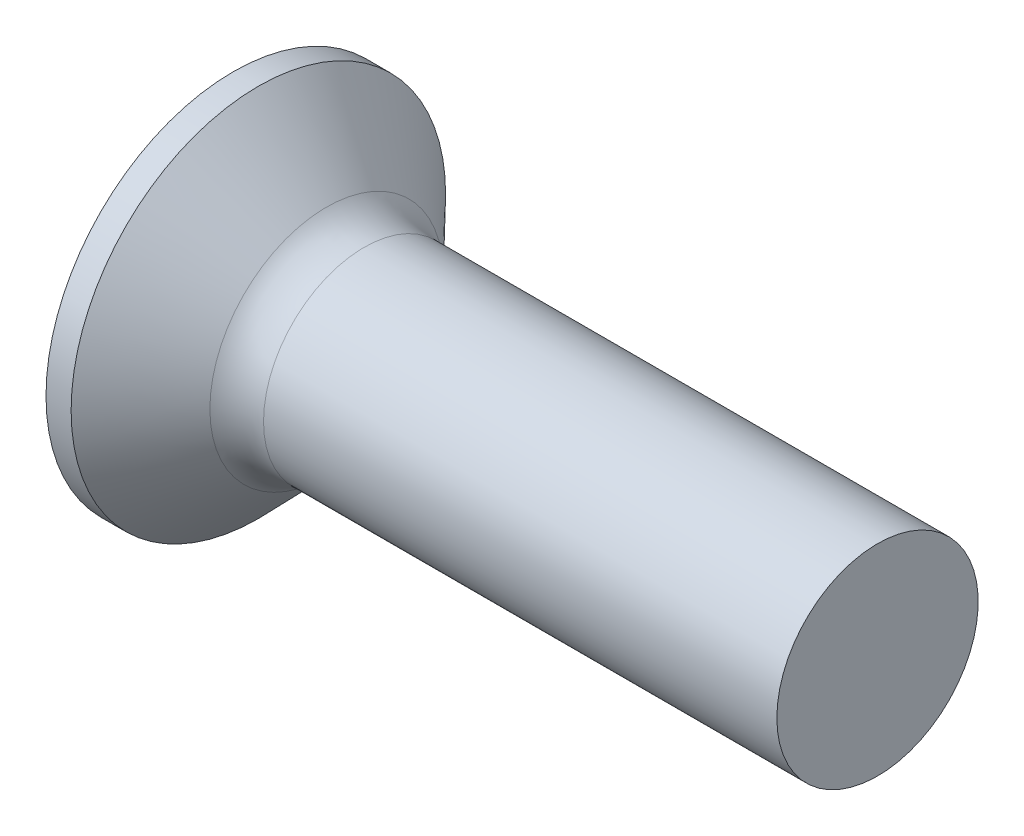
SolidWorks part; units mm, degrees
ref_plane "Plane1" through (0, 0, 0) normal (0, 0, 1) x (1, 0, 0)
ref_plane "Plane2" through (0, 0, 0) normal (0, 1, 0) x (1, 0, 0)
ref_plane "Plane3" through (0, 0, 0) normal (1, 0, 0) x (0, 0, -1)
sketch "BodySke" plane through (0, 0, 0) normal (0, 0, 1) x (1, 0, 0)
  line L0 (0, 0) -> (0, 4.65)
  line L1 (0, 4.65) -> (0.6238, 4.65)
  line L2 (2.7, 2.5) -> (16, 2.5)
  line L3 (16, 2.5) -> (16, 0)
  line L4 (16, 0) -> (0, 0)
  line L5 (-6.35, 0) -> (82.55, 0) construction
  line L6 (2.7, -2.5) -> (16, -2.5) construction
  line L7 (0.6238, -4.65) -> (2.7, -2.5) construction
  line L8 (0.6238, 4.65) -> (2.7, 2.5)
  line L9 (0, -4.65) -> (0.6238, -4.65) construction
  line L10 (3.5, 4.0875) -> (3.5, -5.4375) construction
  line L11 (0, 6.35) -> (0, -3.175) construction
  dimension "Diameter" = 5
  dimension "Length" = 16
  dimension "Head_ht" = 2.7
  dimension "Head_dia" = 9.3
  dimension "Head_ang" = 92
  dimension "D6" = 0.6238
  dimension "Advance" = 0.8
  dimension "Thread_nom" = 16
revolve "Base-Revolve" add sketch "BodySke" angle 360 about L5
cosmetic thread "ThreadCosmetic" [suppressed] parameters "Thread_length"=12.5, "Thread_minor"=4.11
fillet "Fillet1" radius 1.3
sketch "Sketch3" plane through (0, 0, 0) normal (-1, 0, 0) x (0, 0, 1)
  line L0 (-0.515, 2.45) -> (0.515, 2.45)
  line L1 (0.515, 2.45) -> (0.515, -2.45)
  line L2 (0.515, -2.45) -> (-0.515, -2.45)
  line L3 (-0.515, -2.45) -> (-0.515, 2.45)
  dimension "D1" = 2.45
  dimension "Cross_dia" = 4.9
  dimension "D2" = 0.515
  dimension "Cross_width" = 1.03
ref_plane "Plane4" through (3.05, 0, 0) normal (-1, 0, 0) x (0, 0, 1)
sketch "Sketch4" plane through (3.05, 0, 0) normal (-1, 0, 0) x (0, 0, 1)
  line L0 (-0.515, 0.9293) -> (0.515, 0.9293)
  line L3 (0.515, 0.9293) -> (0.515, -0.9293)
  line L4 (0.515, -0.9293) -> (-0.515, -0.9293)
  line L5 (-0.515, -0.9293) -> (-0.515, 0.9293)
  dimension "D1" = 1.03
  dimension "D2" = 1.8587
  dimension "D3" = 0.515
  dimension "D4" = 0.9293
loft "Recess" cut profiles "Sketch3", "Sketch4"
pattern_circular "RecPat" count 2 every 90 about axis through (-6.35, 0, 0) along (1, 0, 0)
sketch "RecCorSke" plane through (0, 0, 0) normal (0, 0, 1) x (1, 0, 0)
  line L0 (-3.175, 0) -> (15.875, 0) construction
  line L2 (0, 0) -> (0, 1.0643)
  line L3 (0, 1.0643) -> (3.05, 0.851)
  line L4 (3.05, 0.851) -> (3.3265, 0)
  line L5 (3.3265, 0) -> (0, 0)
  dimension "Diameter" = 1.702
  dimension "Depth" = 3.05
  dimension "Draft_angle" = 4
  dimension "Bottom_angle" = 18
revolve "RecessCore" cut sketch "RecCorSke" angle 360 about L0
sketch "ThdSchSke" plane through (0, 0, 0) normal (0, 0, 1) x (1, 0, 0)
  line L0 (3.5, -2.055) -> (3.1884, -2.5)
  line L1 (3.5, -2.055) -> (3.8116, -2.5)
  line L2 (3.8116, -2.5) -> (3.8116, -3.125)
  line L3 (-3.175, 0) -> (5.1513, 0) construction
  line L5 (3.8116, -3.125) -> (3.1884, -3.125)
  line L6 (3.1884, -3.125) -> (3.1884, -2.5)
  line L7 (0, 4.65) -> (0, -4.65) construction
  dimension "Thread_minor" = 4.11
  dimension "Diameter" = 5
  dimension "Start" = 3.5
  dimension "SideAngle" = 55
  dimension "VeeAngle" = 70
  dimension "Overcut" = 6.25
revolve "ThreadSchematic" [suppressed] cut sketch "ThdSchSke" angle 360 about L3
pattern_linear "ThdSchPat" [suppressed]
equation "\"D1@Sketch3\" = \"Cross_dia@Sketch3\" / 2"
equation "\"D2@Sketch3\" = \"Cross_width@Sketch3\" / 2"
equation "\"Depth@RecCorSke\" = \"Cross_depth@Plane4\""
equation "\"D1@Sketch4\" = \"Cross_width@Sketch3\""
equation "\"D2@Sketch4\" = \"Cross_dia@Sketch3\" - 2.0 * \"Cross_depth@Plane4\" * tan(26.5  * 0.017453292)"
equation "\"D3@Sketch4\" = \"D1@Sketch4\" / 2"
equation "\"D4@Sketch4\" = \"D2@Sketch4\" / 2"
equation "\"Thread_length@ThreadCosmetic\" = ((sgn( (\"Length@BodySke\" - \"Advance@BodySke\" * 1.0 - \"Head_ht@BodySke\" ) - \"Thread_nom@BodySke\" )-1)*( (\"Length@BodySke\" - \"Advance@BodySke\" * 1.0 - \"Head_ht@BodySke\" ) - \"Thread_nom@BodySke\" ))/-2+ \"Thread_nom@BodySke\""
equation "\"Thread_minor@ThdSchSke\" = \"Thread_minor@ThreadCosmetic\""
equation "\"Diameter@ThdSchSke\" = \"Diameter@BodySke\""
equation "\"Overcut@ThdSchSke\" = \"Diameter@BodySke\" * 1.25"
equation "\"Start@ThdSchSke\" = 0.000001 + \"Length@BodySke\" - \"Thread_length@ThreadCosmetic\"  '---Countersunk---"
equation "\"Num_threads@ThdSchPat\" = int( \"Thread_length@ThreadCosmetic\" / \"Advance@BodySke\" + 0.999 )  + 1"
equation "\"Advance@ThdSchPat\" = \"Thread_length@ThreadCosmetic\" /  (\"Num_threads@ThdSchPat\" - 1) 'relax it"
